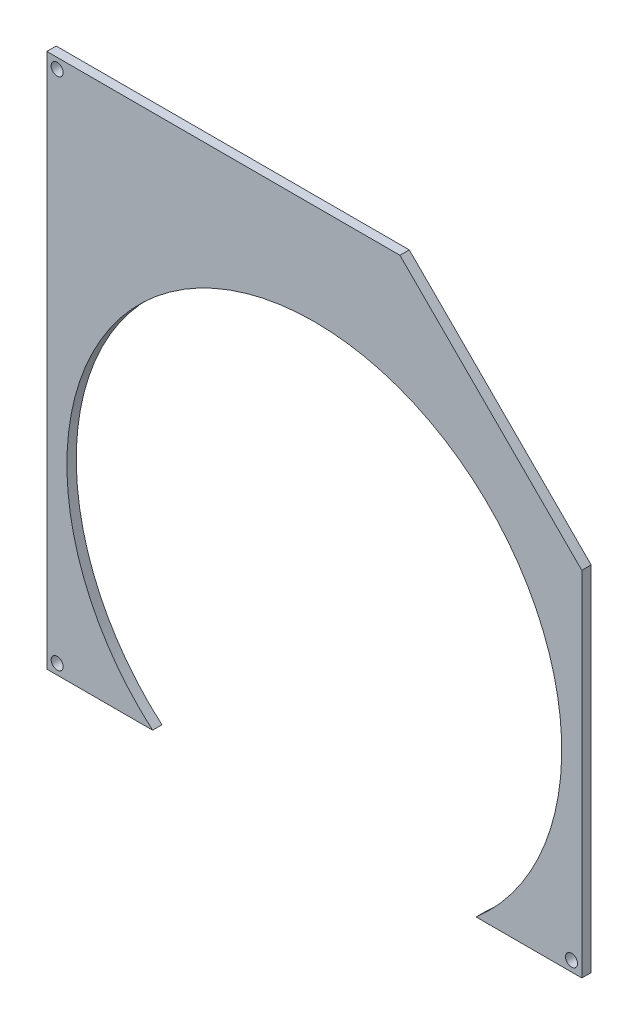
SolidWorks part; units mm, degrees
material "Polyester Resin"
ref_plane "Ground" through (0, 0, 0) normal (0, 0, 1) x (1, 0, 0)
ref_plane "Right" through (0, 0, 0) normal (0, 1, 0) x (1, 0, 0)
ref_plane "Front" through (0, 0, 0) normal (1, 0, 0) x (0, 0, -1)
sketch "Sketch1" plane through (0, 0, 0) normal (0, 0, 1) x (1, 0, 0)
  line L0 (0, 100) -> (0, -100) construction
  line L1 (-100, -100) -> (100, -100)
  line L2 (-100, -100) -> (-100, 100)
  line L3 (-100, 100) -> (100, 100)
  line L4 (100, -100) -> (100, 100)
  line L5 (-100, -100) -> (100, 100) construction
  line L6 (-100, 100) -> (100, -100) construction
  line L8 (32, 100) -> (100, 32)
  circle A0 centre (0, -30) radius 92.5
  circle A1 centre (-96.15, 96.15) radius 2.25
  circle A2 centre (96.15, 96.15) radius 2.25
  circle A3 centre (96.15, -96.15) radius 2.25
  circle A4 centre (-96.15, -96.15) radius 2.25
  point P0 (0, 0)
  dimension "D2" = 185
  dimension "D4" = 4.5
  dimension "D1" = 200
  dimension "D3" = 130
  dimension "D5" = 3.85
  dimension "D6" = 132
  dimension "D7" = 45
extrude "Boss-Extrude1" add sketch "Sketch1" along normal blind 3.5 contours A0 L1 L4 L3 L2 A2 A1 A3 A4
